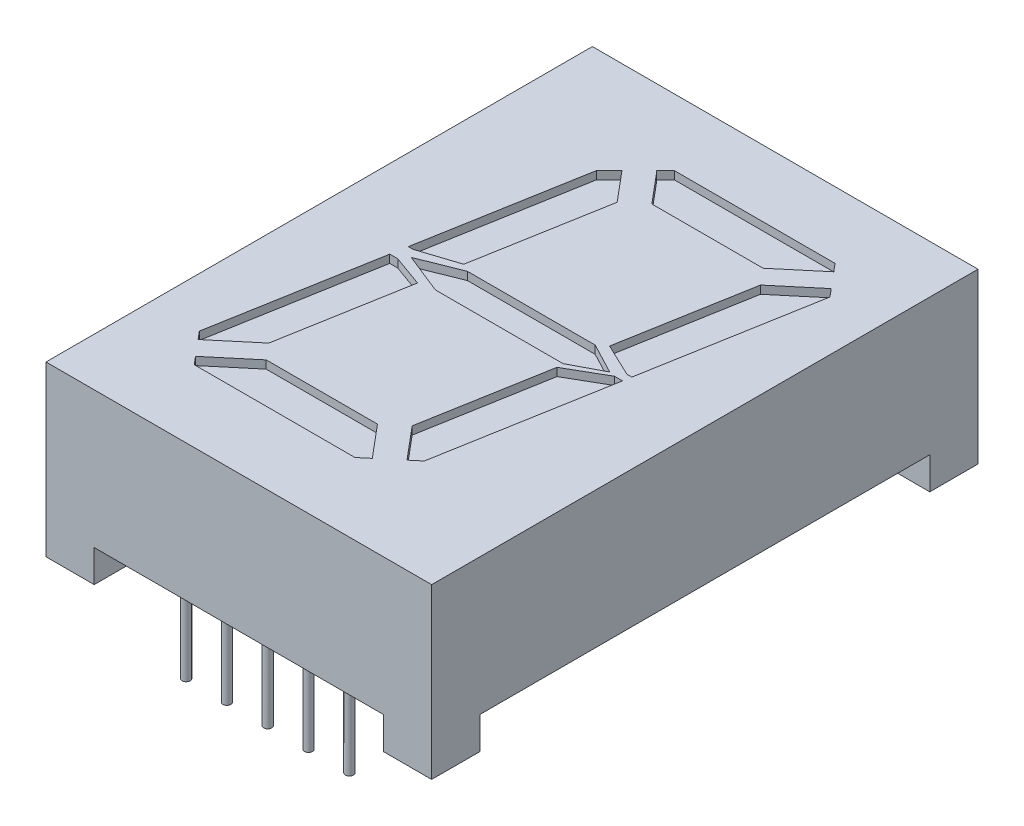
SolidWorks part; units mm, degrees
ref_plane "Front Plane" through (0, 0, 0) normal (0, 0, 1) x (1, 0, 0)
ref_plane "Top Plane" through (0, 0, 0) normal (0, 1, 0) x (1, 0, 0)
ref_plane "Right Plane" through (0, 0, 0) normal (1, 0, 0) x (0, 0, -1)
sketch "Sketch1" plane through (0, 0, 0) normal (0, 1, 0) x (1, 0, 0)
  line L0 (0, 0) -> (0, 15.2) construction
  line L1 (-12, 17) -> (12, 17)
  line L2 (-12, 17) -> (-12, -17)
  line L3 (-12, -17) -> (12, -17)
  line L4 (12, 17) -> (12, -17)
  line L5 (-12, 17) -> (12, -17) construction
  line L6 (-12, -17) -> (12, 17) construction
  line L7 (0, 0) -> (0, -15.2) construction
  line L8 (0, 15.2) -> (12, 15.2) construction
  line L9 (-12, 0) -> (12, 0) construction
  circle A0 centre (0, 15.2) radius 0.25
  circle A1 centre (0, -15.2) radius 0.25
  circle A3 centre (2.54, 15.2) radius 0.25
  circle A4 centre (5.08, 15.2) radius 0.25
  circle A5 centre (-2.54, 15.2) radius 0.25
  circle A6 centre (-5.08, 15.2) radius 0.25
  circle A7 centre (-5.08, -15.2) radius 0.25
  circle A8 centre (-2.54, -15.2) radius 0.25
  circle A9 centre (2.54, -15.2) radius 0.25
  circle A10 centre (5.08, -15.2) radius 0.25
  point P0 (0, 0)
  point P30 (0, 0)
  point P31 (0, 0)
  dimension "D5" = 0.5
  dimension "D6" = 0.5
  dimension "D7" = 0.5
  dimension "D8" = 2.54
  dimension "D9" = 0.5
  dimension "D10" = 2.54
  dimension "D1" = 24
  dimension "D2" = 34
  dimension "D3" = 15.2
  dimension "D4" = 15.2
extrude "Boss-Extrude1" add sketch "Sketch1" against normal blind 10.5 contours L2 L1 L4 L3
sketch "Sketch3" plane through (0, -10.5, 0) normal (0, -1, 0) x (1, 0, 0)
  line L0 (0, 0) -> (0, 15.2) construction
  line L1 (-12, 17) -> (12, 17)
  line L2 (-12, 17) -> (-12, -17)
  line L3 (-12, -17) -> (12, -17)
  line L4 (12, 17) -> (12, -17)
  line L5 (-12, 17) -> (12, -17) construction
  line L6 (-12, -17) -> (12, 17) construction
  line L7 (0, 0) -> (0, -15.2) construction
  line L8 (0, 15.2) -> (12, 15.2) construction
  line L9 (-12, 0) -> (12, 0) construction
  circle A0 centre (0, 15.2) radius 0.25
  circle A1 centre (0, -15.2) radius 0.25
  circle A2 centre (2.54, 15.2) radius 0.25
  circle A3 centre (5.08, 15.2) radius 0.25
  circle A4 centre (-2.54, 15.2) radius 0.25
  circle A5 centre (-5.08, 15.2) radius 0.25
  circle A6 centre (-5.08, -15.2) radius 0.25
  circle A7 centre (-2.54, -15.2) radius 0.25
  circle A8 centre (2.54, -15.2) radius 0.25
  circle A9 centre (5.08, -15.2) radius 0.25
  point P0 (0, 0)
extrude "Boss-Extrude2" add sketch "Sketch3" along normal blind 4 contours A5 | A4 | A0 | A2 | A3 | A6 | A7 | A1 | A8 | A9
sketch "Sketch4" plane through (12, 0, 0) normal (1, 0, 0) x (0, 0, -1)
  line L0 (0, 0) -> (0, -10.5) construction
  line L1 (17, 0) -> (-17, 0) construction
  line L2 (17, -10.5) -> (-17, -10.5) construction
  line L3 (17, -10.5) -> (17, 0) construction
  line L4 (0, -10.5) -> (14, -10.5)
  line L5 (0, -10.5) -> (0, -8.5)
  line L6 (0, -8.5) -> (14, -8.5)
  line L7 (14, -10.5) -> (14, -8.5)
  line L8 (0, -10.5) -> (-14, -10.5)
  line L9 (0, -10.5) -> (0, -8.5)
  line L10 (0, -8.5) -> (-14, -8.5)
  line L11 (-14, -10.5) -> (-14, -8.5)
  line L12 (-17, -10.5) -> (-17, 0) construction
  line M9 (-17, -10.5) -> (17, -10.5)
  dimension "D1" = 3
  dimension "D2" = 3
  dimension "D3" = 2
  dimension "D4" = 2
extrude "Cut-Extrude1" cut sketch "Sketch4" against normal blind 30 contours L11 L5 L10 M9 | L7 L6 L5 M9
sketch "Sketch5" plane through (0, 0, 17) normal (0, 0, 1) x (1, 0, 0)
  line L0 (0, 0) -> (0, -10.5) construction
  line L1 (-12, -10.5) -> (12, -10.5) construction
  line L2 (12, -10.5) -> (12, 0) construction
  line L3 (0, -10.5) -> (9, -10.5)
  line L4 (0, -10.5) -> (0, -8.5)
  line L5 (0, -8.5) -> (9, -8.5)
  line L6 (9, -10.5) -> (9, -8.5)
  line L7 (0, -10.5) -> (-9, -10.5)
  line L8 (0, -10.5) -> (0, -8.5)
  line L9 (0, -8.5) -> (-9, -8.5)
  line L10 (-9, -10.5) -> (-9, -8.5)
  line L11 (-12, -10.5) -> (-12, 0) construction
  line M9 (-12, -10.5) -> (12, -10.5)
  dimension "D1" = 3
  dimension "D2" = 3
  dimension "D3" = 2
  dimension "D4" = 2
extrude "Cut-Extrude2" cut sketch "Sketch5" against normal blind 43 contours L6 L5 L4 M9 | L10 L4 L9 M9
sketch "Sketch6" plane through (0, -10.5, 0) normal (0, 1, 0) x (1, 0, 0)
  circle A0 centre (0, -15.2) radius 0.25
  circle A1 centre (2.54, -15.2) radius 0.25
  circle A2 centre (5.08, -15.2) radius 0.25
  circle A3 centre (-5.08, -15.2) radius 0.25
  circle A4 centre (-2.54, -15.2) radius 0.25
  circle A5 centre (5.08, 15.2) radius 0.25
  circle A6 centre (2.54, 15.2) radius 0.25
  circle A7 centre (0, 15.2) radius 0.25
  circle A8 centre (-2.54, 15.2) radius 0.25
  circle A9 centre (-5.08, 15.2) radius 0.25
extrude "Boss-Extrude3" add sketch "Sketch6" along normal up to surface (2 mm away) up to face at (0, -8.5, 0)
sketch "Sketch7" plane through (0, 0, 0) normal (0, 1, 0) x (1, 0, 0)
  line L0 (0, 17) -> (0, -17) construction
  line L1 (-12, 17) -> (12, 17) construction
  line L2 (-12, -17) -> (12, -17) construction
  line L3 (-12, 0) -> (12, 0) construction
  line L4 (-12, 17) -> (-12, -17) construction
  line L5 (12, 17) -> (12, -17) construction
  line L6 (2.4444, 12.6961) -> (9.2394, 12.8653) construction
  line L7 (2.4444, 12.6961) -> (-4.7606, 12.8653) construction
  line L8 (0.2057, -0.0005) -> (3.2033, 17) construction
  line L9 (0.2057, -0.0005) -> (-2.7918, -17) construction
  line L10 (-1.9978, -12.4967) -> (-9.2394, -12.5347) construction
  line L11 (-1.9978, -12.4967) -> (4.7606, -12.5347) construction
  line L12 (-7.2394, -12.5347) -> (2.7606, -12.5347)
  line L13 (-8.8921, -10.5651) -> (-5.1888, 10.4372)
  line L14 (5.1079, -10.5651) -> (8.8921, 10.8957)
  line L15 (-2.7606, 12.8653) -> (7.2394, 12.8653)
  line L16 (-1.9978, -12.4967) -> (-1.5636, -10.0347) construction
  line L17 (-5.26, -10.0347) -> (1.6629, -10.0347)
  line L18 (-6.0863, -9.0499) -> (-2.8365, 9.3805)
  line L19 (2.8365, -9.0499) -> (6.0863, 9.3805)
  line L20 (-1.6629, 10.3653) -> (5.26, 10.3653)
  line L21 (-5.1888, 10.4372) -> (-2.7606, 12.8653)
  line L22 (-8.8921, -10.5651) -> (-7.2394, -12.5347)
  line L23 (2.7606, -12.5347) -> (5.1079, -10.5651)
  line L24 (7.2394, 12.8653) -> (8.8921, 10.8957)
  line L25 (-2.8365, 9.3805) -> (-1.6629, 10.3653)
  line L26 (6.0863, 9.3805) -> (5.26, 10.3653)
  line L27 (1.6629, -10.0347) -> (2.8365, -9.0499)
  line L28 (-5.26, -10.0347) -> (-6.0863, -9.0499)
  line L29 (-6.0863, -9.0499) -> (-5.26, -10.0347)
  line L30 (-6.0863, -9.0499) -> (-8.5822, -11.1442)
  line L31 (-5.26, -10.0347) -> (-7.7559, -12.129)
  line L32 (-8.5822, -11.1442) -> (-7.7559, -12.129)
  line L33 (1.6629, -10.0347) -> (2.8365, -9.0499)
  line L34 (1.6629, -10.0347) -> (3.4228, -12.1321)
  line L35 (2.8365, -9.0499) -> (4.5965, -11.1473)
  line L36 (3.4228, -12.1321) -> (4.5965, -11.1473)
  line L37 (6.0863, 9.3805) -> (5.26, 10.3653)
  line L38 (6.0863, 9.3805) -> (8.3832, 11.3078)
  line L39 (5.26, 10.3653) -> (7.5568, 12.2926)
  line L40 (8.3832, 11.3078) -> (7.5568, 12.2926)
  line L41 (-2.8365, 9.3805) -> (-1.6629, 10.3653)
  line L42 (-2.8365, 9.3805) -> (-4.3852, 11.2261)
  line L43 (-1.6629, 10.3653) -> (-3.2115, 12.2109)
  line L44 (-4.3852, 11.2261) -> (-3.2115, 12.2109)
  line L45 (7, 0.1653) -> (7.0434, 0.4115)
  line L46 (7, 0.1653) -> (6.9566, -0.0809)
  line L47 (7.0434, 0.4115) -> (6.7434, 0.4115)
  line L48 (6.7434, 0.4115) -> (4.6783, 1.3951)
  line L49 (6.9566, -0.0809) -> (6.4566, -0.0809)
  line L50 (6.4566, -0.0809) -> (4.1875, -1.3884)
  line L51 (-7.0291, 0) -> (-6.9423, 0.4924)
  line L52 (-7.0291, 0) -> (-7.116, -0.4924)
  line L53 (-6.9423, 0.4924) -> (-6.6423, 0.4924)
  line L54 (-7.116, -0.4924) -> (-6.616, -0.4924)
  line L55 (-6.616, -0.4924) -> (-4.6989, -1.1813)
  line L56 (-6.6423, 0.4924) -> (-4.267, 1.2682)
  line L57 (-3.767, 0.9995) -> (-6.2733, 0)
  line L58 (-3.767, 0.9995) -> (4.1783, 0.9995)
  line L59 (-3.767, 0.9995) -> (-3.767, -1.0005)
  line L60 (-3.767, -1.0005) -> (4.1783, -1.0005)
  line L61 (4.1783, 0.9995) -> (4.1783, -1.0005)
  line L62 (-3.767, 0.9995) -> (4.1783, -1.0005) construction
  line L63 (-3.767, -1.0005) -> (4.1783, 0.9995) construction
  line L64 (-6.2733, 0) -> (-3.767, -1.0005)
  line L65 (4.1783, 0.9995) -> (6.0806, 0)
  line L66 (6.0806, 0) -> (4.1783, -1.0005)
  point P24 (-6.26, -10.0347)
  point P25 (2.6629, -10.0347)
  point P28 (6.26, 10.3653)
  point P32 (-2.6629, 10.3653)
  point P68 (4.6392, 1.0024)
  point P71 (4.2457, -1.1864)
  point P72 (-4.6391, -1.0005)
  point P73 (-4.6391, -1.0005)
  point P74 (-4.3049, 0.9995)
  point P75 (-4.267, 1.2276)
  point P76 (-4.6806, -1.0759)
  point P77 (4.1988, -1.3608)
  point P78 (0, 0)
  point P79 (4.6783, 1.3149)
  point P80 (-4.6989, -1.1813)
  dimension "D23" = 0.3
  dimension "D1" = 6.797
  dimension "D2" = 7.207
  dimension "D3" = 12.6961
  dimension "D4" = 10
  dimension "D5" = 10
  dimension "D6" = 7.2417
  dimension "D7" = 6.7585
  dimension "D8" = 12.4967
  dimension "D9" = 2.5
  dimension "D10" = 2.5
  dimension "D11" = 10
  dimension "D12" = 2.5
  dimension "D13" = 80
  dimension "D14" = 14
  dimension "D15" = 25.7918
  dimension "D16" = 4.7606
  dimension "D17" = 2.5
  dimension "D18" = 2.5
  dimension "D19" = 2
  dimension "D20" = 45
  dimension "D21" = 0.25
  dimension "D22" = 0.25
  dimension "D27" = 0.5
  dimension "D32" = 0.3476
  dimension "D34" = 0.5
  dimension "D35" = 0.5
  dimension "D36" = 0.3
  dimension "D37" = 0.5
  dimension "D40" = 2
  dimension "D41" = 0.5
  dimension "D42" = 0.5
extrude "Cut-Extrude3" cut sketch "Sketch7" against normal blind 0.5 contours L53 L56 L18 L42 L44 L43 L20 L39 L40 L38 L19 L48 L47 L14 L24 L15 L21 L13 | L55 L54 L13 L22 L30 L18 | L34 L17 L31 L22 L12 L23 | L49 L50 L19 L35 L23 L14 | L61 L58 L59 L60 | L18 L64 L59 L57 | L57 L64 L18 | L66 L19 L65 L61 | L66 L65 L19
sketch "Sketch8" plane through (0, -0.5, 0) normal (0, 1, 0) x (1, 0, 0)
  line L0 (7.5568, 12.2926) -> (7.6525, 12.3729)
  line L1 (7.2394, 12.8653) -> (8.8921, 10.8957) construction
  line L2 (8.3832, 11.3078) -> (8.4789, 11.3881)
  line L3 (8.4789, 11.3881) -> (7.6525, 12.3729)
  line L4 (7.5568, 12.2926) -> (8.3832, 11.3078)
  line L5 (-4.3852, 11.2261) -> (-4.3925, 11.2334)
  line L6 (-5.1888, 10.4372) -> (-2.7606, 12.8653) construction
  line L7 (-3.2115, 12.2109) -> (-3.3133, 12.3127)
  line L8 (-3.3133, 12.3127) -> (-4.3925, 11.2334)
  line L9 (-4.3852, 11.2261) -> (-3.2115, 12.2109)
extrude "Boss-Extrude4" add sketch "Sketch8" along normal up to surface (0.5 mm away) up to face at (-6.9813, 0, 5.4731)
